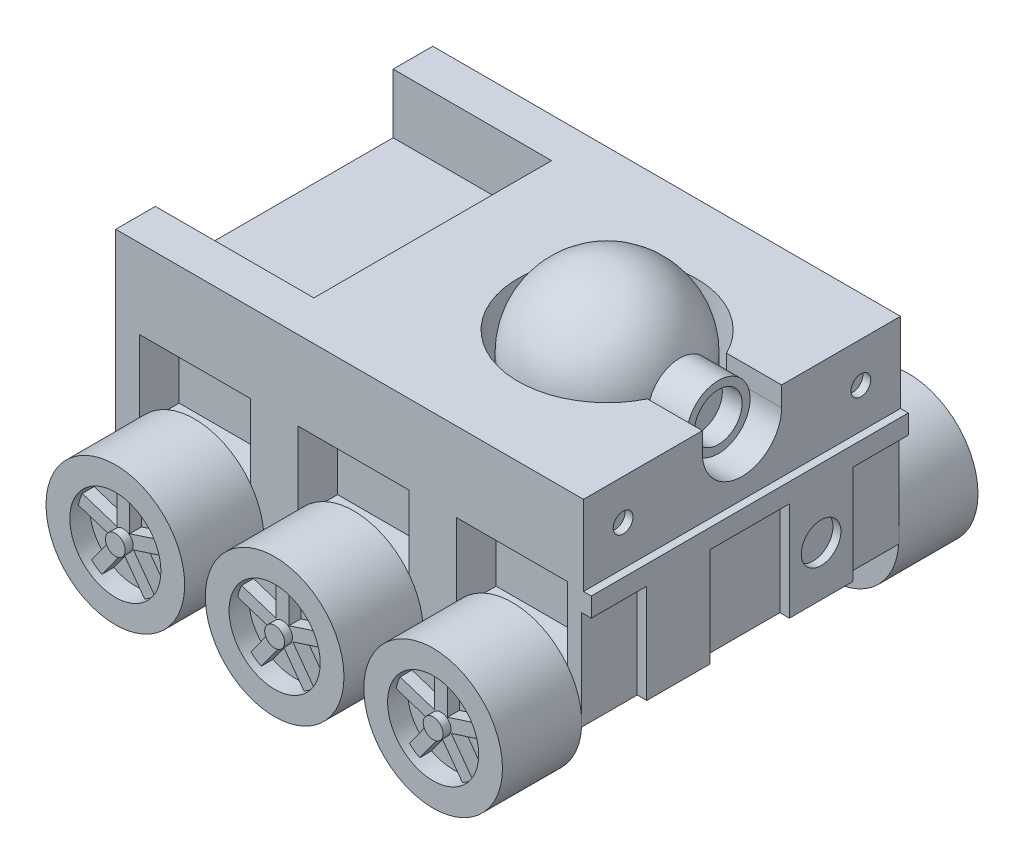
SolidWorks part; units mm, degrees
ref_plane "Front Plane" through (0, 0, 0) normal (0, 0, 1) x (1, 0, 0)
ref_plane "Top Plane" through (0, 0, 0) normal (0, 1, 0) x (1, 0, 0)
ref_plane "Right Plane" through (0, 0, 0) normal (1, 0, 0) x (0, 0, -1)
sketch "Sketch1" plane through (0, 0, 0) normal (0, 0, 1) x (1, 0, 0)
  line L1 (-38.1, 15.875) -> (38.1, 15.875)
  line L2 (-38.1, 15.875) -> (-38.1, -15.875)
  line L3 (-38.1, -15.875) -> (38.1, -15.875)
  line L4 (38.1, 15.875) -> (38.1, -15.875)
  line L5 (-38.1, 15.875) -> (38.1, -15.875) construction
  line L6 (-38.1, -15.875) -> (38.1, 15.875) construction
  point P0 (0, 0)
  dimension "D1" = 76.2
  dimension "D2" = 31.75
extrude "Boss-Extrude1" add sketch "Sketch1" along normal mid plane 50.8
sketch "Sketch2" plane through (0, 15.875, 0) normal (0, 1, 0) x (1, 0, 0)
  line L0 (28.0388, 6.35) -> (38.1, 6.35)
  line L1 (38.1, -25.4) -> (38.1, 25.4) construction
  line L2 (15.24, 0) -> (38.1, 0) construction
  line L3 (28.0388, -6.35) -> (38.1, -6.35)
  line L4 (38.1, 6.35) -> (38.1, -6.35)
  arc A0 (28.0388, 6.35) -> (28.0388, -6.35) centre (15.24, 0) ccw
  dimension "D1" = 28.575
  dimension "D2" = 6.35
  dimension "D3" = 22.86
extrude "Cut-Extrude1" cut sketch "Sketch2" against normal blind 9.525
sketch "Sketch3" plane through (0, 6.35, 0) normal (0, 1, 0) x (1, 0, 0)
  circle A0 centre (15.24, 0) radius 12.7
  dimension "D1" = 25.4
extrude "Boss-Extrude2" add sketch "Sketch3" along normal blind 6.35
sketch "Sketch4" plane through (0, 0, 0) normal (0, 0, 1) x (1, 0, 0)
  line L0 (27.94, 12.7) -> (2.54, 12.7) construction
  line L1 (15.24, 12.7) -> (15.24, 25.4)
  line L2 (15.24, 12.7) -> (27.94, 12.7)
  arc A0 (27.94, 12.7) -> (15.24, 25.4) centre (15.24, 12.7) ccw
  dimension "D1" = 25.4
revolve "Revolve1" add sketch "Sketch4" angle 360 about L1
ref_plane "Plane1" through (33.0694, 0, 0) normal (1, 0, 0) x (0, 0, -1)
sketch "Sketch5" plane through (33.0694, 0, 0) normal (1, 0, 0) x (0, 0, -1)
  line L0 (-12.7, 12.7) -> (12.7, 12.7) construction
  circle A0 centre (0, 12.7) radius 5.08
  dimension "D1" = 10.16
extrude "Boss-Extrude3" add sketch "Sketch5" against normal up to surface (6.1897 mm away)
sketch "Sketch6" plane through (33.0694, 0, 0) normal (1, 0, 0) x (0, 0, -1)
  circle A0 centre (0, 12.7) radius 3.81
  circle A1 centre (0, 12.7) radius 5.08 construction
  dimension "D1" = 1.27
extrude "Cut-Extrude2" cut sketch "Sketch6" against normal blind 3.175
sketch "Sketch7" plane through (38.1, 0, 0) normal (1, 0, 0) x (0, 0, -1)
  line L9 (6.35, 6.35) -> (6.35, 15.875)
  line L10 (-6.35, 15.875) -> (-6.35, 6.35)
  line L11 (-6.35, 6.35) -> (6.35, 6.35)
  line L12 (6.35, 6.35) -> (6.35, 12.7)
  line L13 (-6.35, 12.7) -> (-6.35, 6.35)
  line L14 (-6.35, 6.35) -> (6.35, 6.35)
  circle A2 centre (0, 12.7) radius 6.35
  arc A3 (-6.35, 12.7) -> (6.35, 12.7) centre (0, 12.7) ccw
  line M6 (6.35, 15.875) -> (6.35, 6.35)
  line M7 (6.35, 6.35) -> (-6.35, 6.35)
  line M8 (-6.35, 6.35) -> (-6.35, 15.875)
  dimension "D1" = 0
  dimension "D2" = 1.27
extrude "Boss-Extrude4" add sketch "Sketch7" against normal up to vertex (10.0612 mm away) contours A3 L14 M8 | A3 M7 M6
sketch "Sketch11" plane through (0, 0, 25.4) normal (0, 0, 1) x (1, 0, 0)
  line L0 (36.8553, 15.875) -> (36.8553, 3.08)
  line L1 (38.1, 15.875) -> (-38.1, 15.875) construction
  line L2 (36.8553, 3.08) -> (38.1, 3.08)
  line L3 (38.1, -15.875) -> (38.1, 15.875) construction
  line L4 (38.1, 3.08) -> (38.1, 15.875)
  line L5 (38.1, 15.875) -> (36.8553, 15.875)
extrude "Cut-Extrude5" cut sketch "Sketch11" against normal through all
sketch "Sketch12" plane through (38.1, 0, 0) normal (1, 0, 0) x (0, 0, -1)
  line L0 (-25.4, -15.875) -> (25.4, -15.875) construction
  line L1 (-16.51, -15.875) -> (-25.4, -15.875)
  line L2 (-16.51, -15.875) -> (-16.51, 0)
  line L3 (-16.51, 0) -> (-25.4, 0)
  line L4 (-25.4, -15.875) -> (-25.4, 0)
  line L5 (-16.51, -15.875) -> (-25.4, 0) construction
  line L6 (-16.51, 0) -> (-25.4, -15.875) construction
  line L7 (-25.4, -15.875) -> (-25.4, 3.08) construction
  line L9 (25.4, -15.875) -> (16.51, -15.875)
  line L10 (25.4, -15.875) -> (25.4, 0)
  line L11 (25.4, 0) -> (16.51, 0)
  line L12 (16.51, -15.875) -> (16.51, 0)
  line L13 (25.4, -15.875) -> (16.51, 0) construction
  line L14 (25.4, 0) -> (16.51, -15.875) construction
  line L15 (-6.35, -15.875) -> (6.35, -15.875)
  line L16 (-6.35, -15.875) -> (-6.35, 0)
  line L17 (-6.35, 0) -> (6.35, 0)
  line L18 (6.35, -15.875) -> (6.35, 0)
  line L19 (-6.35, -15.875) -> (6.35, 0) construction
  line L20 (-6.35, 0) -> (6.35, -15.875) construction
  point P4 (-20.955, -7.9375)
  point P13 (20.955, -7.9375)
  point P19 (0, -7.9375)
  dimension "D1" = 8.89
  dimension "D2" = 8.89
  dimension "D3" = 10.16
  dimension "D4" = 10.16
extrude "Cut-Extrude6" cut sketch "Sketch12" against normal blind 1.524
sketch "Sketch15" plane through (0, 15.875, 0) normal (0, 1, 0) x (1, 0, 0)
  line L0 (-38.1, -25.4) -> (-38.1, 25.4) construction
  line L1 (-38.1, 19.05) -> (-12.7, 19.05)
  line L2 (-38.1, 19.05) -> (-38.1, -19.05)
  line L3 (-38.1, -19.05) -> (-12.7, -19.05)
  line L4 (-12.7, 19.05) -> (-12.7, -19.05)
  line L5 (-38.1, 19.05) -> (-12.7, -19.05) construction
  line L6 (-38.1, -19.05) -> (-12.7, 19.05) construction
  point P4 (-25.4, 0)
  point P7 (0, 0)
  dimension "D1" = 25.4
  dimension "D2" = 38.1
extrude "Cut-Extrude9" cut sketch "Sketch15" against normal blind 9.525
sketch "Sketch16" plane through (38.1, 0, 0) normal (1, 0, 0) x (0, 0, -1)
  circle A0 centre (11.43, -7.9375) radius 3.175
  dimension "D1" = 6.35
extrude "Cut-Extrude10" cut sketch "Sketch16" against normal blind 1.27
sketch "Sketch17" plane through (36.8553, 0, 0) normal (1, 0, 0) x (0, 0, -1)
  line L0 (-25.4, 15.875) -> (-25.4, 3.08) construction
  line L1 (25.4, 15.875) -> (25.4, 3.08) construction
  circle A0 centre (-19.05, 9.4775) radius 1.5875
  circle A1 centre (19.05, 9.4775) radius 1.5875
  dimension "D1" = 3.175
  dimension "D2" = 3.175
  dimension "D3" = 6.35
  dimension "D4" = 6.35
extrude "Cut-Extrude11" cut sketch "Sketch17" against normal blind 1.27
sketch "Sketch8" plane through (0, 0, 25.4) normal (0, 0, 1) x (1, 0, 0)
  line L0 (0, 0) -> (0, 11.7565) construction
  circle A0 centre (0.0621, -15.24) radius 11.1125
  circle A1 centre (25.4621, -15.24) radius 11.1125
  circle A2 centre (-25.4621, -15.24) radius 11.1125
  dimension "D1" = 22.225
  dimension "D2" = 22.225
  dimension "D3" = 25.4
  dimension "D4" = 15.24
extrude "Boss-Extrude5" add sketch "Sketch8" along normal blind 12.7
sketch "Sketch9" plane through (0, 0, 25.4) normal (0, 0, 1) x (1, 0, 0)
  line L0 (16.51, 3.175) -> (34.29, 3.175)
  line L1 (-8.89, 3.175) -> (8.89, 3.175)
  line L2 (-8.89, 3.175) -> (-8.89, -8.6561)
  line L3 (16.51, 3.175) -> (16.51, -8.6561)
  line L4 (8.89, 3.175) -> (8.89, -8.4905)
  line L5 (-8.89, 3.175) -> (8.89, -15.875) construction
  line L6 (-8.89, -15.875) -> (8.89, 3.175) construction
  line L7 (34.29, 3.175) -> (34.29, -8.4905)
  line L8 (-34.29, 3.175) -> (-16.51, 3.175)
  line L9 (-34.29, 3.175) -> (-34.29, -8.6561)
  line L10 (-16.51, 3.175) -> (-16.51, -8.4905)
  arc A1 (34.29, -8.4905) -> (16.51, -8.6561) centre (25.4621, -15.24) ccw
  arc A2 (11.1564, -15.875) -> (-11.0323, -15.875) centre (0.0621, -15.24) ccw
  arc A3 (8.89, -8.4905) -> (-8.89, -8.6561) centre (0.0621, -15.24) ccw
  arc A4 (-16.51, -8.4905) -> (-34.29, -8.6561) centre (-25.3379, -15.24) ccw
  point P0 (0, -6.35)
  dimension "D1" = 19.05
  dimension "D2" = 6.35
  dimension "D3" = 17.78
  dimension "D4" = 0
  dimension "D5" = 2
  dimension "D6" = 2
extrude "Cut-Extrude3" cut sketch "Sketch9" against normal blind 6.35
sketch "Sketch10" plane through (0, 3.175, 0) normal (0, -1, 0) x (1, 0, 0)
  line L8 (34.29, 25.4) -> (16.51, 25.4)
  line L9 (16.51, 25.4) -> (16.51, 19.05)
  line L10 (16.51, 19.05) -> (34.29, 19.05)
  line L11 (34.29, 19.05) -> (34.29, 25.4)
  line L12 (34.29, 25.4) -> (16.51, 25.4)
  line L13 (16.51, 25.4) -> (16.51, 19.05)
  line L14 (16.51, 19.05) -> (34.29, 19.05)
  line L15 (34.29, 19.05) -> (34.29, 25.4)
  line L20 (8.89, 25.4) -> (-8.89, 25.4)
  line L21 (-8.89, 25.4) -> (-8.89, 19.05)
  line L22 (-8.89, 19.05) -> (8.89, 19.05)
  line L23 (8.89, 19.05) -> (8.89, 25.4)
  line L24 (8.89, 25.4) -> (-8.89, 25.4)
  line L25 (-8.89, 25.4) -> (-8.89, 19.05)
  line L26 (-8.89, 19.05) -> (8.89, 19.05)
  line L27 (8.89, 19.05) -> (8.89, 25.4)
  line L32 (-16.51, 25.4) -> (-34.29, 25.4)
  line L33 (-34.29, 25.4) -> (-34.29, 19.05)
  line L34 (-34.29, 19.05) -> (-16.51, 19.05)
  line L35 (-16.51, 19.05) -> (-16.51, 25.4)
  line L36 (-16.51, 25.4) -> (-34.29, 25.4)
  line L37 (-34.29, 25.4) -> (-34.29, 19.05)
  line L38 (-34.29, 19.05) -> (-16.51, 19.05)
  line L39 (-16.51, 19.05) -> (-16.51, 25.4)
  dimension "D1" = 0
  dimension "D2" = 0
  dimension "D3" = 0
extrude "Cut-Extrude4" cut sketch "Sketch10" along normal blind 12.7
sketch "Sketch13" plane through (0, 0, 38.1) normal (0, 0, 1) x (1, 0, 0)
  line L0 (25.4621, -16.9685) -> (22.0335, -21.6876)
  line L1 (23.8182, -15.7741) -> (18.2706, -13.9716)
  line L2 (27.106, -15.7741) -> (32.6536, -13.9716)
  line L3 (0.0621, -16.9685) -> (-3.3665, -21.6876)
  line L4 (-1.5818, -15.7741) -> (-7.1294, -13.9716)
  line L5 (25.4621, -16.9685) -> (28.8907, -21.6876)
  line L6 (27.106, -15.7741) -> (30.5346, -20.4932)
  line L7 (26.4781, -13.8416) -> (32.0257, -12.0391)
  line L8 (1.706, -15.7741) -> (7.2536, -13.9716)
  line L9 (26.4781, -13.8416) -> (26.4781, -8.0085)
  line L10 (0.0621, -16.9685) -> (3.4907, -21.6876)
  line L11 (24.4461, -13.8416) -> (18.8985, -12.0391)
  line L12 (24.4461, -13.8416) -> (24.4461, -8.0085)
  line L13 (1.706, -15.7741) -> (5.1346, -20.4932)
  line L14 (23.8182, -15.7741) -> (20.3896, -20.4932)
  line L15 (1.0781, -13.8416) -> (6.6257, -12.0391)
  line L16 (-25.4621, -16.9685) -> (-28.8907, -21.6876)
  line L17 (1.0781, -13.8416) -> (1.0781, -8.0085)
  line L18 (-27.106, -15.7741) -> (-32.6536, -13.9716)
  line L19 (-23.8182, -15.7741) -> (-18.2706, -13.9716)
  line L20 (-25.4621, -16.9685) -> (-22.0335, -21.6876)
  line L21 (-0.9539, -13.8416) -> (-6.5015, -12.0391)
  line L22 (-23.8182, -15.7741) -> (-20.3896, -20.4932)
  line L23 (-0.9539, -13.8416) -> (-0.9539, -8.0085)
  line L24 (-24.4461, -13.8416) -> (-18.8985, -12.0391)
  line L25 (-24.4461, -13.8416) -> (-24.4461, -8.0085)
  line L26 (-26.4781, -13.8416) -> (-32.0257, -12.0391)
  line L27 (-1.5818, -15.7741) -> (-5.0104, -20.4932)
  line L28 (-26.4781, -13.8416) -> (-26.4781, -8.0085)
  line L29 (-27.106, -15.7741) -> (-30.5346, -20.4932)
  arc A1 (6.6257, -12.0391) -> (1.0781, -8.0085) centre (0.0621, -15.24) ccw
  circle A2 centre (0.0621, -15.24) radius 7.3025
  arc A3 (-0.9539, -8.0085) -> (-6.5015, -12.0391) centre (0.0621, -15.24) ccw
  arc A4 (5.1346, -20.4932) -> (7.2536, -13.9716) centre (0.0621, -15.24) ccw
  arc A5 (-3.3665, -21.6876) -> (3.4907, -21.6876) centre (0.0621, -15.24) ccw
  arc A6 (-7.1294, -13.9716) -> (-5.0104, -20.4932) centre (0.0621, -15.24) ccw
  arc A7 (32.0257, -12.0391) -> (26.4781, -8.0085) centre (25.4621, -15.24) ccw
  arc A8 (24.4461, -8.0085) -> (18.8985, -12.0391) centre (25.4621, -15.24) ccw
  arc A9 (30.5346, -20.4932) -> (32.6536, -13.9716) centre (25.4621, -15.24) ccw
  arc A10 (22.0335, -21.6876) -> (28.8907, -21.6876) centre (25.4621, -15.24) ccw
  arc A11 (18.2706, -13.9716) -> (20.3896, -20.4932) centre (25.4621, -15.24) ccw
  arc A12 (-18.8985, -12.0391) -> (-24.4461, -8.0085) centre (-25.4621, -15.24) ccw
  arc A13 (-26.4781, -8.0085) -> (-32.0257, -12.0391) centre (-25.4621, -15.24) ccw
  arc A14 (-20.3896, -20.4932) -> (-18.2706, -13.9716) centre (-25.4621, -15.24) ccw
  arc A15 (-28.8907, -21.6876) -> (-22.0335, -21.6876) centre (-25.4621, -15.24) ccw
  arc A16 (-32.6536, -13.9716) -> (-30.5346, -20.4932) centre (-25.4621, -15.24) ccw
  point P11 (0.0621, -15.24)
  point P26 (25.4621, -15.24)
  point P45 (-25.4621, -15.24)
  dimension "D1" = 3.81
extrude "Cut-Extrude7" cut sketch "Sketch13" against normal blind 3.175
sketch "Sketch14" plane through (0, 0, 38.1) normal (0, 0, 1) x (1, 0, 0)
  circle A0 centre (0.0621, -15.24) radius 7.3025
  circle A1 centre (0.0621, -15.24) radius 1.5875
  circle A2 centre (25.4621, -15.24) radius 7.3025
  circle A3 centre (25.4621, -15.24) radius 1.5875
  circle A4 centre (-25.4621, -15.24) radius 7.3025
  circle A5 centre (-25.4621, -15.24) radius 1.5875
  dimension "D1" = 3.175
  dimension "D2" = 3.175
  dimension "D3" = 3.175
extrude "Cut-Extrude8" cut sketch "Sketch14" against normal blind 1.27
mirror "Mirror1" about plane through (0, 0, 0) normal (0, 0, 1) of "Boss-Extrude5", "Cut-Extrude3", "Cut-Extrude4", "Cut-Extrude7", "Cut-Extrude8"
